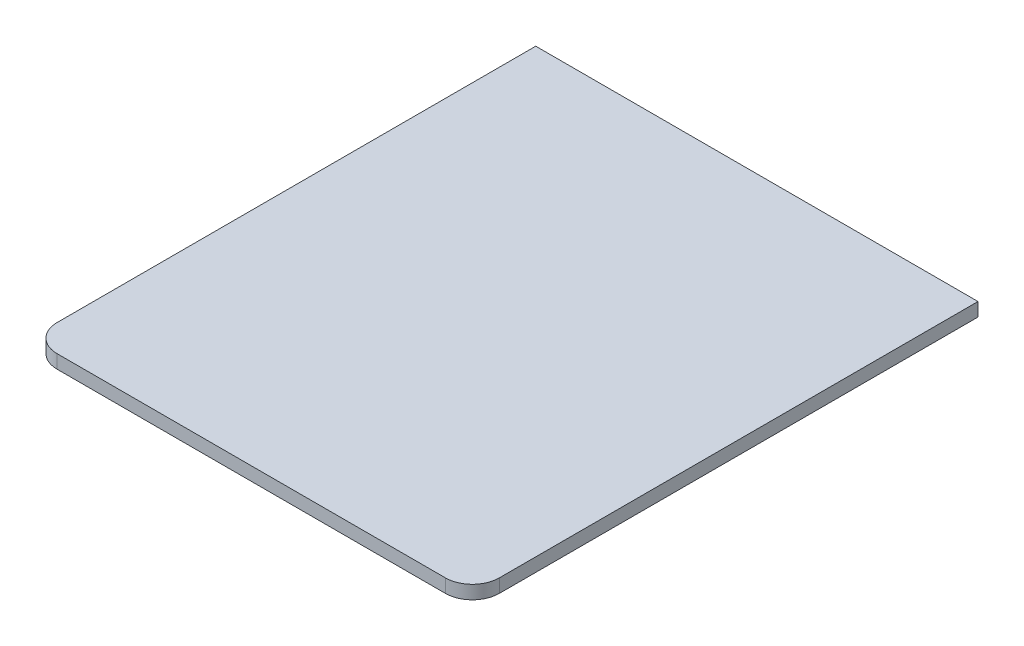
SolidWorks part; units mm, degrees
ref_plane "前视基准面" through (0, 0, 0) normal (0, 0, 1) x (1, 0, 0)
ref_plane "上视基准面" through (0, 0, 0) normal (0, 1, 0) x (1, 0, 0)
ref_plane "右视基准面" through (0, 0, 0) normal (1, 0, 0) x (0, 0, -1)
other "Configuration Table"
sketch "草图1" plane through (0, 0, 0) normal (0, 1, 0) x (1, 0, 0)
  line L1 (0, 0) -> (32.8, 0)
  line L2 (0, 0) -> (0, 37.5)
  line L3 (0, 37.5) -> (32.8, 37.5)
  line L4 (32.8, 0) -> (32.8, 37.5)
  dimension "D1" = 37.5
  dimension "D2" = 32.8
extrude "凸台-拉伸1" add sketch "草图1" against normal blind 1
fillet "圆角1" radius 2 2 edges at (32.8, -0.5, 0) (0, -0.5, 0)
